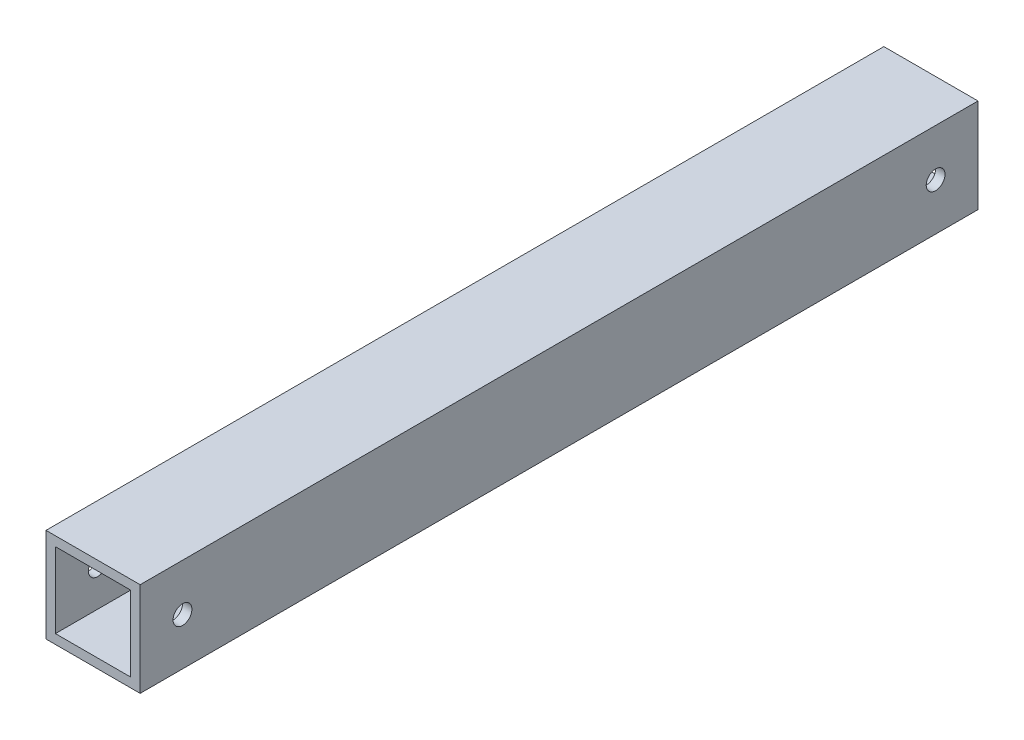
SolidWorks part; units mm, degrees
ref_plane "前视基准面" through (0, 0, 0) normal (0, 0, 1) x (1, 0, 0)
ref_plane "上视基准面" through (0, 0, 0) normal (0, 1, 0) x (1, 0, 0)
ref_plane "右视基准面" through (0, 0, 0) normal (1, 0, 0) x (0, 0, -1)
sketch "草图1" plane through (0, 0, 0) normal (0, 0, 1) x (1, 0, 0)
  line L1 (-10, 10) -> (10, 10)
  line L2 (-10, 10) -> (-10, -10)
  line L3 (-10, -10) -> (10, -10)
  line L4 (10, 10) -> (10, -10)
  line L5 (-10, 10) -> (10, -10) construction
  line L6 (-10, -10) -> (10, 10) construction
  line L7 (-8, 8) -> (8, 8)
  line L8 (-8, 8) -> (-8, -8)
  line L9 (-8, -8) -> (8, -8)
  line L10 (8, 8) -> (8, -8)
  line L11 (-8, 8) -> (8, -8) construction
  line L12 (-8, -8) -> (8, 8) construction
  point P0 (0, 0)
  point P5 (0, 0)
  dimension "D1" = 20
  dimension "D2" = 16
extrude "凸台-拉伸1" add sketch "草图1" along normal mid plane 180
sketch "草图2" plane through (10, 0, 0) normal (1, 0, 0) x (0, 0, -1)
  line L0 (-1000, 0) -> (49000, 0) construction
  line L2 (-90, -10) -> (-90, 10) construction
  line L3 (90, -10) -> (90, 10) construction
  circle A1 centre (80, 0) radius 2
  circle A2 centre (-80, 0) radius 2
  dimension "D1" = 10
  dimension "D2" = 4
  dimension "D3" = 4
  dimension "D7" = 10
extrude "切除-拉伸1" cut sketch "草图2" against normal through all
sketch "草图3" plane through (10, 0, 0) normal (1, 0, 0) x (0, 0, -1)
  line L0 (0, 0) -> (0, 21.23) construction
  line L1 (-90, 10) -> (-89, 10)
  line L2 (-90, 10) -> (90, 10) construction
  line L3 (-89, 10) -> (-89, -15.2991)
  line L4 (-89, -15.2991) -> (-95.5014, -15.2991)
  line L5 (-95.5014, -15.2991) -> (-95.5014, 10)
  line L6 (-95.5014, 10) -> (-90, 10)
  line L7 (-90, -10) -> (-90, 10) construction
  line L8 (89, -15.2991) -> (95.5014, -15.2991)
  line L9 (95.5014, -15.2991) -> (95.5014, 10)
  line L10 (90, 10) -> (89, 10)
  line L11 (95.5014, 10) -> (90, 10)
  line L12 (89, 10) -> (89, -15.2991)
  dimension "D1" = 1
extrude "切除-拉伸2" cut sketch "草图3" against normal through all
